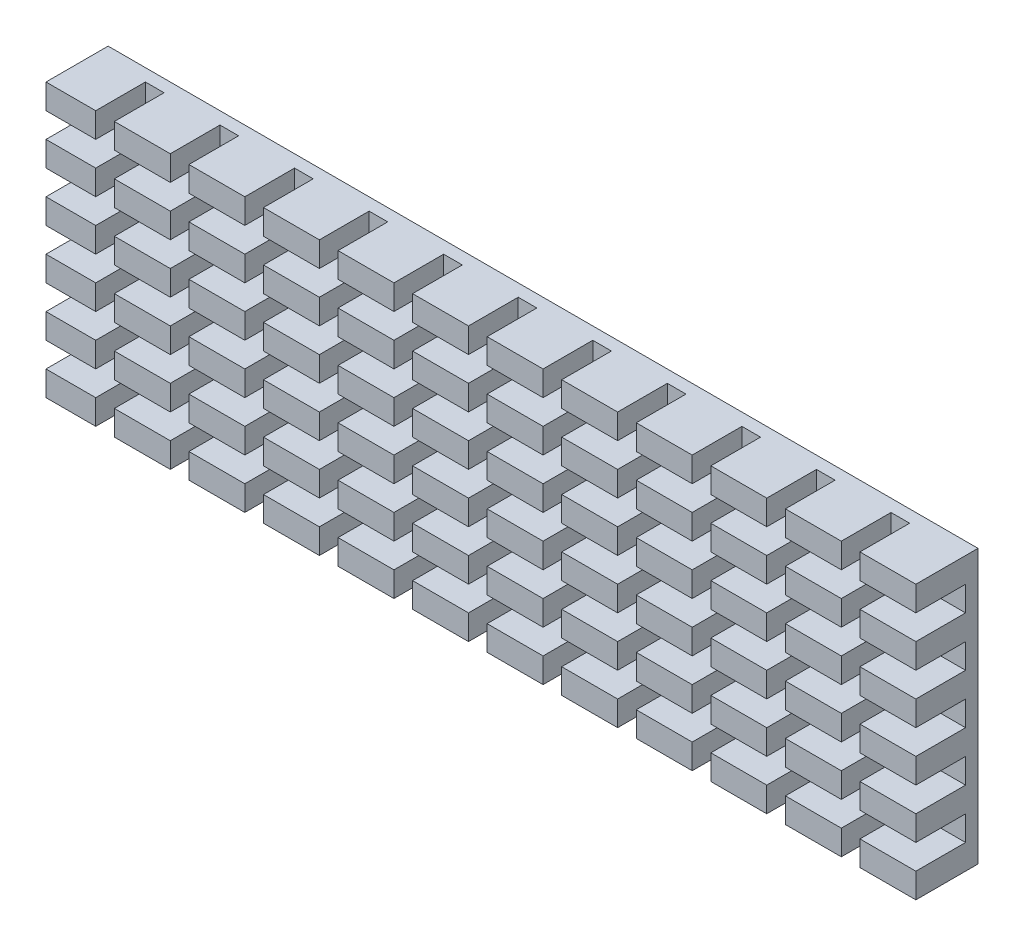
SolidWorks part; units mm, degrees
ref_plane "Top Plane" through (0, 0, 0) normal (0, 0, 1) x (1, 0, 0)
ref_plane "Front Plane" through (0, 0, 0) normal (0, 1, 0) x (1, 0, 0)
ref_plane "Right Plane" through (0, 0, 0) normal (1, 0, 0) x (0, 0, -1)
sketch "Sketch1" plane through (0, 0, 0) normal (0, 0, 1) x (1, 0, 0)
  line L1 (-35, -11) -> (35, -11)
  line L2 (-35, -11) -> (-35, 11)
  line L3 (-35, 11) -> (35, 11)
  line L4 (35, -11) -> (35, 11)
  line L5 (-35, -11) -> (35, 11) construction
  line L6 (-35, 11) -> (35, -11) construction
  point P0 (0, 0)
  dimension "D1" = 22
  dimension "D2" = 70
extrude "Boss-Extrude1" add sketch "Sketch1" along normal blind 5
sketch "Sketch3" plane through (0, 0, 0) normal (0, 0, 1) x (1, 0, 0)
  line L0 (-35, 11) -> (-35, -11) construction
  line L1 (-35, 1) -> (35, 1)
  line L2 (-35, 1) -> (-35, -1)
  line L3 (-35, -1) -> (35, -1)
  line L4 (35, 1) -> (35, -1)
  line L5 (35, -11) -> (35, 11) construction
  point P8 (35, 0)
  point P9 (35, 0)
  dimension "D1" = 2
extrude "Cut-Extrude1" cut sketch "Sketch3" along normal through all from offset 1
pattern_linear "LPattern1" count 4 spacing 4 along (0, 1, 0) count 4 spacing 4 along (0, -1, 0) of "Cut-Extrude1"
sketch "Sketch4" plane through (0, 0, 0) normal (0, 0, 1) x (1, 0, 0)
  line L0 (35, 11) -> (-35, 11) construction
  line L1 (-31, 11) -> (-29.5, 11)
  line L2 (-31, 11) -> (-31, -11)
  line L3 (-31, -11) -> (-29.5, -11)
  line L4 (-29.5, 11) -> (-29.5, -11)
  line L5 (-35, -11) -> (35, -11) construction
  dimension "D1" = 1.5
  dimension "D2" = 4
extrude "Cut-Extrude2" cut sketch "Sketch4" along normal through all from offset 1
pattern_linear "LPattern2" count 12 spacing 6 along (1, 0, 0) of "Cut-Extrude2"
